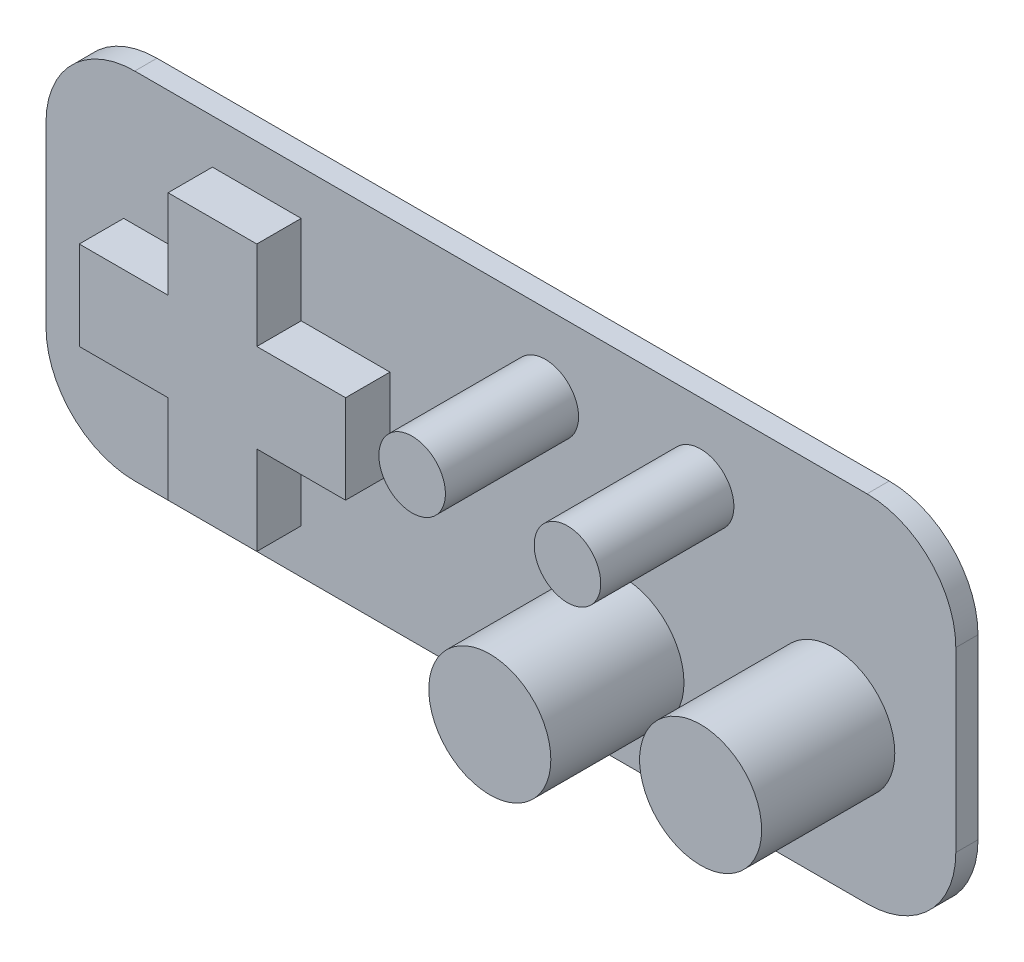
SolidWorks part; units mm, degrees
ref_plane "前视基准面" through (0, 0, 0) normal (0, 0, 1) x (1, 0, 0)
ref_plane "上视基准面" through (0, 0, 0) normal (0, 1, 0) x (1, 0, 0)
ref_plane "右视基准面" through (0, 0, 0) normal (1, 0, 0) x (0, 0, -1)
sketch "草图1" plane through (0, 0, 0) normal (0, 0, 1) x (1, 0, 0)
  line L1 (-15.7826, 8.75) -> (17.2174, 8.75)
  line L2 (-19.7826, 4.75) -> (-19.7826, -3.25)
  line L3 (-15.7826, -7.25) -> (17.2174, -7.25)
  line L4 (21.2174, 4.75) -> (21.2174, -3.25)
  arc A0 (-15.7826, 8.75) -> (-19.7826, 4.75) centre (-15.7826, 4.75) ccw
  arc A1 (17.2174, 8.75) -> (21.2174, 4.75) centre (17.2174, 4.75) cw
  arc A2 (17.2174, -7.25) -> (21.2174, -3.25) centre (17.2174, -3.25) ccw
  arc A3 (-19.7826, -3.25) -> (-15.7826, -7.25) centre (-15.7826, -3.25) ccw
  point P6 (-19.7826, 8.75)
  point P9 (21.2174, 8.75)
  point P14 (-19.7826, -7.25)
  dimension "D3" = 4
  dimension "D4" = 4
  dimension "D1" = 41
  dimension "D2" = 16
extrude "凸台-拉伸1" add sketch "草图1" along normal blind 1
sketch "草图3" plane through (0, 0, 1) normal (0, 0, 1) x (1, 0, 0)
  line L0 (-15.7826, -7.25) -> (17.2174, -7.25) construction
  line L1 (21.2174, -3.25) -> (21.2174, 4.75) construction
  line L2 (-12.2826, 6.75) -> (-12.2826, 2.75)
  line L3 (-12.2826, 2.75) -> (-16.2826, 2.75)
  line L4 (-16.2826, 2.75) -> (-16.2826, -1.25)
  line L5 (-16.2826, -1.25) -> (-12.2826, -1.25)
  line L6 (-12.2826, -1.25) -> (-12.2826, -5.25)
  line L7 (-12.2826, -5.25) -> (-8.2826, -5.25)
  line L8 (-8.2826, -5.25) -> (-8.2826, -1.25)
  line L9 (-8.2826, -1.25) -> (-4.2826, -1.25)
  line L10 (-4.2826, -1.25) -> (-4.2826, 2.75)
  line L11 (-4.2826, 2.75) -> (-8.2826, 2.75)
  line L12 (-8.2826, 2.75) -> (-8.2826, 6.75)
  line L13 (-8.2826, 6.75) -> (-12.2826, 6.75)
  line L14 (-10.2826, 18.1091) -> (-10.2826, -49981.8909) construction
  line L15 (-1013.0365, 0.75) -> (48986.9635, 0.75) construction
  circle A0 centre (6.2174, -2.75) radius 2.75
  circle A1 centre (15.7174, -0.75) radius 2.75
  circle A2 centre (2.7174, 5.25) radius 1.5
  circle A3 centre (9.7174, 5.25) radius 1.5
  point P27 (-10.2826, 0.75)
  dimension "D1" = 5.5
  dimension "D3" = 4.5
  dimension "D5" = 15
  dimension "D6" = 3
  dimension "D2" = 9.5
  dimension "D4" = 2
  dimension "D7" = 7
  dimension "D8" = 6
  dimension "D9" = 6
  dimension "D10" = 4
  dimension "D11" = 4
  dimension "D12" = 16.5
  dimension "D13" = 3.5
extrude "凸台-拉伸2" add sketch "草图3" along normal blind 6 contours A2 | A3 | A0 | A1
sketch "草图4" plane through (0, 0, 0) normal (0, 0, 1) x (1, 0, 0)
  line L2 (-12.2826, 6.75) -> (-12.2826, 2.75)
  line L3 (-12.2826, 2.75) -> (-16.2826, 2.75)
  line L4 (-16.2826, 2.75) -> (-16.2826, -1.25)
  line L5 (-16.2826, -1.25) -> (-12.2826, -1.25)
  line L6 (-12.2826, -1.25) -> (-12.2826, -5.25)
  line L7 (-12.2826, -5.25) -> (-8.2826, -5.25)
  line L8 (-8.2826, -5.25) -> (-8.2826, -1.25)
  line L9 (-8.2826, -1.25) -> (-4.2826, -1.25)
  line L10 (-4.2826, -1.25) -> (-4.2826, 2.75)
  line L11 (-4.2826, 2.75) -> (-8.2826, 2.75)
  line L12 (-8.2826, 2.75) -> (-8.2826, 6.75)
  line L13 (-8.2826, 6.75) -> (-12.2826, 6.75)
  line L14 (-10.2826, 18.1091) -> (-10.2826, -49981.8909) construction
  line L15 (-1011.0365, 0.75) -> (48988.9635, 0.75) construction
  circle A0 centre (6.2174, -2.75) radius 2.75
  circle A1 centre (15.7174, -0.75) radius 2.75
  circle A2 centre (2.7174, 5.25) radius 1.5
  circle A3 centre (9.7174, 5.25) radius 1.5
  circle A4 centre (15.7174, -0.75) radius 2.75 construction
  point P27 (-10.2826, 0.75)
  dimension "D1" = 5.5
  dimension "D6" = 3
  dimension "D2" = 9.5
  dimension "D4" = 2
  dimension "D7" = 7
  dimension "D8" = 6
  dimension "D9" = 6
  dimension "D10" = 4
  dimension "D11" = 4
  dimension "D12" = 16.5
  dimension "D13" = 3.5
extrude "凸台-拉伸3" add sketch "草图4" along normal blind 3 contours L12 L13 L2 L3 L4 L5 L6 L7 L8 L9 L10 L11
